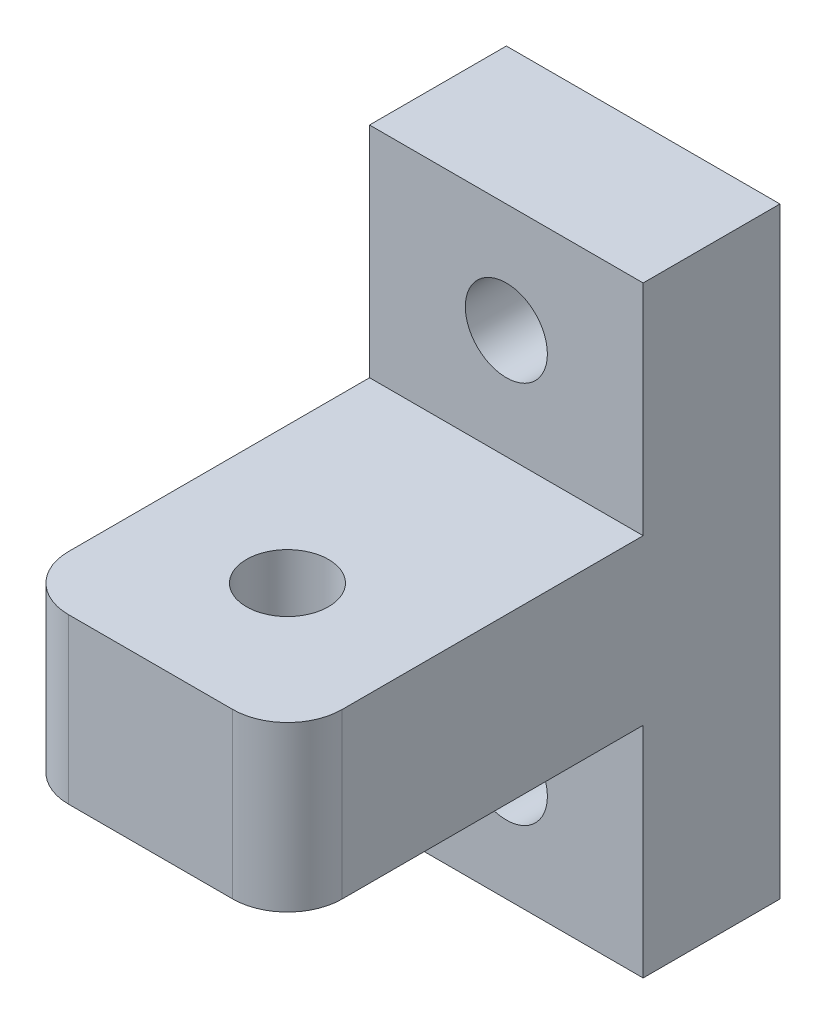
SolidWorks part; units mm, degrees
material "3.0205 (EN-AW 1200)"
ref_plane "Alzado" through (0, 0, 0) normal (0, 0, 1) x (1, 0, 0)
ref_plane "Planta" through (0, 0, 0) normal (0, 1, 0) x (1, 0, 0)
ref_plane "Vista lateral" through (0, 0, 0) normal (1, 0, 0) x (0, 0, -1)
sketch "Croquis1" plane through (0, 0, 0) normal (0, 0, 1) x (1, 0, 0)
  line L1 (-5, -11) -> (5, -11)
  line L2 (-5, -11) -> (-5, 11)
  line L3 (-5, 11) -> (5, 11)
  line L4 (5, -11) -> (5, 11)
  line L5 (-5, -11) -> (5, 11) construction
  line L6 (-5, 11) -> (5, -11) construction
  point P0 (0, 0)
  dimension "D1" = 10
  dimension "D2" = 22
extrude "Saliente-Extruir1" add sketch "Croquis1" along normal blind 5
sketch "Croquis2" plane through (0, 0, 5) normal (0, 0, 1) x (1, 0, 0)
  line L0 (5, -11) -> (5, 11) construction
  line L1 (-5, -3) -> (5, -3)
  line L2 (-5, -3) -> (-5, 3)
  line L3 (-5, 3) -> (5, 3)
  line L4 (5, -3) -> (5, 3)
  line L5 (-5, -3) -> (5, 3) construction
  line L6 (-5, 3) -> (5, -3) construction
  point P0 (0, 0)
  dimension "D1" = 6
extrude "Saliente-Extruir2" add sketch "Croquis2" along normal blind 13
fillet "Redondeo1" radius 2 2 edges at (-5, 0, 18) (5, 0, 18)
sketch "Croquis3" plane through (0, -3, 0) normal (0, -1, 0) x (1, 0, 0)
  line L0 (-3, 18) -> (3, 18) construction
  circle A0 centre (0, 13) radius 1.5
  point P4 (0, 18)
  dimension "D2" = 3
  dimension "D1" = 5
extrude "Cortar-Extruir1" cut sketch "Croquis3" against normal blind 13
sketch "Croquis4" plane through (0, 0, 5) normal (0, 0, 1) x (1, 0, 0)
  circle A0 centre (0, -7) radius 1.5
  circle A1 centre (0, 7) radius 1.5
  dimension "D1" = 3
  dimension "D2" = 3
extrude "Cortar-Extruir2" cut sketch "Croquis4" against normal blind 13
